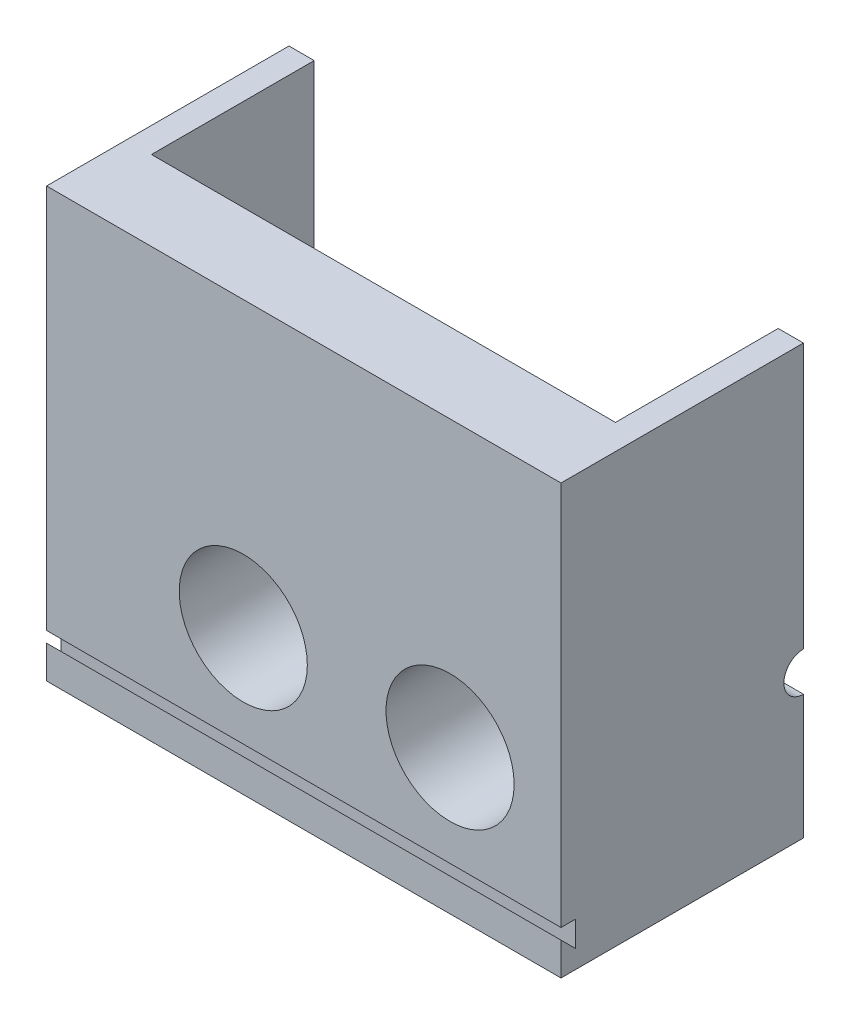
SolidWorks part; units mm, degrees
ref_plane "Front Plane" through (0, 0, 0) normal (0, 0, 1) x (1, 0, 0)
ref_plane "Top Plane" through (0, 0, 0) normal (0, 1, 0) x (1, 0, 0)
ref_plane "Right Plane" through (0, 0, 0) normal (1, 0, 0) x (0, 0, -1)
sketch "Sketch2" plane through (0, 0, 0) normal (0, 1, 0) x (1, 0, 0)
  line L1 (-46, -32.265) -> (46, -32.265)
  line L2 (-46, -32.265) -> (-46, 32.265)
  line L3 (-46, 32.265) -> (46, 32.265)
  line L4 (46, -32.265) -> (46, 32.265)
  line L5 (-46, -32.265) -> (46, 32.265) construction
  line L6 (-46, 32.265) -> (46, -32.265) construction
  line L11 (-12.2964, -8.6248) -> (31.4076, 22.0297) construction
  line L12 (-23.9905, 11.7) -> (23.9905, -11.7) construction
  line L17 (51, -48.065) -> (-51, -48.065)
  line L18 (51, -48.065) -> (51, 48.065)
  line L19 (51, 48.065) -> (-51, 48.065)
  line L20 (-51, -48.065) -> (-51, 48.065)
  line L21 (51, -48.065) -> (-51, 48.065) construction
  line L22 (51, 48.065) -> (-51, -48.065) construction
  point P0 (0, 0)
  point P6 (0, 0)
  point P11 (0, 0)
  point P12 (0, 0)
  dimension "D1" = 92
  dimension "D2" = 96.13
  dimension "D3" = 102
  dimension "D4" = 64.53
extrude "Boss-Extrude1" add sketch "Sketch2" along normal blind 85
sketch "Sketch8" plane through (0, 0, 48.065) normal (0, 0, 1) x (1, 0, 0)
  line L1 (51, 85) -> (51, 0) construction
  line L2 (-51, 0) -> (51, 0) construction
  circle A0 centre (-12, 28.575) radius 12.7
  circle A2 centre (29, 28.575) radius 12.7
  dimension "D1" = 25.4
  dimension "D3" = 25.4
  dimension "D2" = 63
  dimension "D4" = 22
  dimension "D5" = 28.575
  dimension "D6" = 28.575
extrude "Cut-Extrude7" cut sketch "Sketch8" against normal blind 20
sketch "Sketch9" plane through (0, 0, -48.065) normal (0, 0, -1) x (-1, 0, 0)
  line L0 (-51, 85) -> (-51, 0) construction
  circle A0 centre (-31, 31.7) radius 10
  circle A1 centre (29, 31.7) radius 10
  dimension "D1" = 20
  dimension "D3" = 20
  dimension "D2" = 20
  dimension "D4" = 60
extrude "Cut-Extrude8" cut sketch "Sketch9" against normal blind 20
sketch "Sketch10" plane through (-51, 0, 0) normal (-1, 0, 0) x (0, 0, 1)
  line L0 (-48.065, 0) -> (48.065, 0) construction
  circle A0 centre (0, 28.575) radius 3.875
  dimension "D1" = 7.75
  dimension "D2" = 28.575
extrude "Cut-Extrude9" cut sketch "Sketch10" against normal through all
sketch "Sketch11" plane through (-51, 0, 0) normal (-1, 0, 0) x (0, 0, 1)
  line L0 (0, -7.5668) -> (0, 66.0853) construction
  line L7 (0, 85) -> (0, 0)
  line L20 (0, 85) -> (-48.065, 85)
  line L21 (-48.065, 85) -> (-48.065, 0)
  line L22 (-48.065, 0) -> (0, 0)
extrude "Cut-Extrude11" cut sketch "Sketch11" against normal through all
sketch "Sketch12" plane through (0, 0, 0) normal (0, 0, -1) x (-1, 0, 0)
  line L0 (0, -6.7198) -> (0, 71.9034) construction
  line L1 (-70.3197, 31.7) -> (72.5125, 31.7) construction
  line L2 (-48.5, 85) -> (-48.5, 32.45) construction
  line L3 (-51, 85) -> (-46, 85) construction
  line L4 (-46, 32.45) -> (-51, 32.45) construction
  circle A0 centre (-48.5, 58.725) radius 1.6
  circle A1 centre (-48.5, 4.675) radius 1.6
  circle A2 centre (48.5, 4.675) radius 1.6
  circle A3 centre (48.5, 58.725) radius 1.6
  dimension "D1" = 3.2
extrude "Cut-Extrude12" cut sketch "Sketch12" against normal blind 10
sketch "Sketch14" plane through (0, 0, 32.265) normal (0, 0, -1) x (-1, 0, 0)
  circle A7 centre (-29, 28.575) radius 15.5
  circle A10 centre (12, 28.575) radius 15.5
  circle A11 centre (-29, 28.575) radius 12.7
  circle A12 centre (12, 28.575) radius 12.7
  dimension "D1" = 31
  dimension "D2" = 31
extrude "Boss-Extrude2" add sketch "Sketch14" along normal blind 10
fillet "Fillet1" radius 1.5 2 edges at (-24.7, 28.575, 22.265) (16.3, 28.575, 22.265)
sketch "Sketch15" plane through (51, 0, 0) normal (1, 0, 0) x (0, 0, -1)
  line L0 (-48.065, 6.5) -> (-45.2366, 3.6716)
  line L1 (-48.065, 85) -> (-48.065, 0) construction
  line L2 (-45.2366, 3.6716) -> (-45.2366, 8.6716)
  line L3 (-45.2366, 8.6716) -> (-48.065, 8.6716)
  line L4 (-48.065, 8.6716) -> (-48.065, 6.5)
  dimension "D1" = 6.5
  dimension "D2" = 4
  dimension "D3" = 5
  dimension "D4" = 45
extrude "Cut-Extrude13" cut sketch "Sketch15" against normal through all
